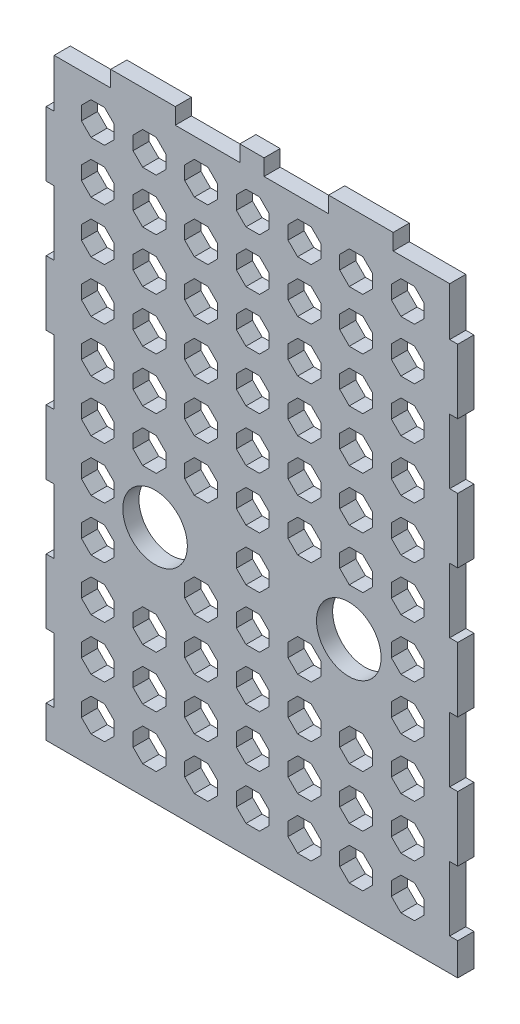
SolidWorks part; units mm, degrees
material "Oak"
ref_plane "Front Plane" through (0, 0, 0) normal (0, 0, 1) x (1, 0, 0)
ref_plane "Top Plane" through (0, 0, 0) normal (0, 1, 0) x (1, 0, 0)
ref_plane "Right Plane" through (0, 0, 0) normal (1, 0, 0) x (0, 0, -1)
sketch "Sketch1" plane through (0, 0, 0) normal (0, 0, 1) x (1, 0, 0)
  line L1 (0, 0) -> (80.9625, 0)
  line L2 (0, 0) -> (0, -120.65)
  line L3 (0, -120.65) -> (80.9625, -120.65)
  line L4 (80.9625, 0) -> (80.9625, -120.65)
extrude "Boss-Extrude1" add sketch "Sketch1" along normal blind 3.175
sketch "Sketch2" plane through (0, 0, 3.175) normal (0, 0, 1) x (1, 0, 0)
  line L0 (0, 0) -> (1.5875, 0)
  line L1 (80.9625, 0) -> (0, 0) construction
  line L2 (1.5875, 0) -> (1.5875, -12.7)
  line L3 (1.5875, -12.7) -> (0, -12.7)
  line L4 (0, 0) -> (0, -120.65) construction
  line L5 (0, -12.7) -> (0, 0)
extrude "Cut-Extrude1" cut sketch "Sketch2" against normal through all
pattern_linear "LPattern1" count 5 spacing 25.4 along (0, -1, 0) of "Cut-Extrude1"
sketch "Sketch5" plane through (0, 0, 3.175) normal (0, 0, 1) x (1, 0, 0)
  line L1 (0, 0) -> (12.7, 0)
  line L2 (0, 0) -> (0, -3.175)
  line L3 (0, -3.175) -> (12.7, -3.175)
  line L4 (12.7, 0) -> (12.7, -3.175)
extrude "Cut-Extrude2" cut sketch "Sketch5" against normal through all
pattern_linear "LPattern2" count 2 spacing 25.4 along (1, 0, 0) of "Cut-Extrude2"
ref_plane "Plane1" through (40.4812, 0, 0) normal (1, 0, 0) x (0, 0, -1)
hole_wizard "Hole1" positions "Sketch7" profile "Sketch6" legacy
sketch "Sketch7" plane through (0, 0, 3.175) normal (0, 0, 1) x (1, 0, 0)
  line L0 (40.4812, -1.7463) -> (40.4812, 1.7463) construction
  line L1 (25.4, 0) -> (12.7, 0) construction
  point P0 (21.4312, -73.66)
  point P11 (19.05, 0)
  dimension "D1" = 19.05
  dimension "D2" = 73.66
sketch "Sketch6" plane through (21.4312, -73.66, 3.175) normal (1, 0, 0) x (0, -1, 0)
  line L0 (0, 0) -> (0, 93.98)
  line L1 (0, 93.98) -> (6.35, 93.98)
  line L2 (6.35, 93.98) -> (6.35, 0)
  line L3 (6.35, 0) -> (0, 0)
  line L4 (0, 110) -> (0, -10) construction
  dimension "Diameter" = 12.7
  dimension "Depth" = 93.98
mirror "Mirror1" about plane through (40.4812, 0, 0) normal (1, 0, 0) of "Hole1", "Cut-Extrude1", "LPattern1", "Cut-Extrude2", "LPattern2"
hole_wizard "Hole2" [suppressed] positions "Sketch9" profile "Sketch8" legacy
sketch "Sketch9" plane through (0, 0, 2.54) normal (0, 0, 1) x (1, 0, 0)
  point P0 (10.16, -10.16)
sketch "Sketch8" plane through (10.16, -10.16, 2.54) normal (1, 0, 0) x (0, -1, 0)
  line L0 (0, 0) -> (0, 2.54)
  line L1 (0, 2.54) -> (3.175, 2.54)
  line L2 (3.175, 2.54) -> (3.175, 0)
  line L3 (3.175, 0) -> (0, 0)
  line L4 (0, 110) -> (0, -10) construction
  dimension "Diameter" = 6.35
  dimension "Depth" = 2.54
pattern_linear "LPattern5" [suppressed] count 11 spacing 10.16 count 7 spacing 10.1071
sketch "Sketch10" plane through (0, 0, 3.175) normal (0, 0, 1) x (1, 0, 0)
  line L1 (13.3794, -8.9952) -> (11.4935, -7.1093)
  line L2 (11.4935, -7.1093) -> (8.8265, -7.1093)
  line L3 (8.8265, -7.1093) -> (6.9406, -8.9952)
  line L4 (6.9406, -8.9952) -> (6.9406, -11.6622)
  line L5 (6.9406, -11.6622) -> (8.8265, -13.5481)
  line L6 (8.8265, -13.5481) -> (11.4935, -13.5481)
  line L7 (11.4935, -13.5481) -> (13.3794, -11.6622)
  line L8 (13.3794, -11.6622) -> (13.3794, -8.9952)
  circle A0 centre (10.16, -10.3287) radius 3.4846 construction
extrude "Cut-Extrude3" cut sketch "Sketch10" against normal through all
pattern_linear "LPattern6" count 7 spacing 10.16 along (1, 0, 0) count 11 spacing 10.16 along (0, -1, 0) skipping (1, 6), (1, 7), (2, 6), (4, 6), (5, 6), (5, 7) of "Cut-Extrude3"
